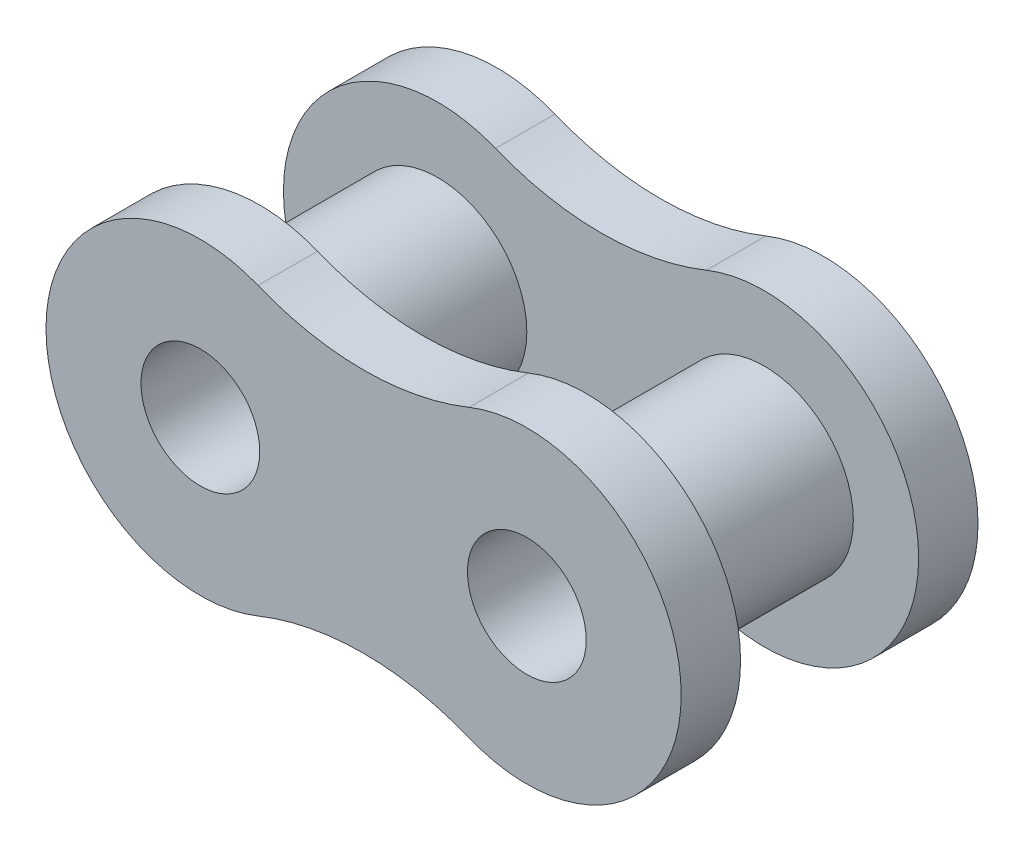
SolidWorks part; units mm, degrees
ref_plane "Front Plane" through (0, 0, 0) normal (0, 0, 1) x (1, 0, 0)
ref_plane "Top Plane" through (0, 0, 0) normal (0, 1, 0) x (1, 0, 0)
ref_plane "Right Plane" through (0, 0, 0) normal (1, 0, 0) x (0, 0, -1)
sketch "Sketch1" plane through (0, 0, 0) normal (0, 0, 1) x (1, 0, 0)
  line L0 (-41.1921, 0) -> (56.3425, 0) construction
  line L2 (-33.0338, 2.6) -> (-33.0338, 8.8923) construction
  arc A0 (-34.8111, 2.4112) -> (-34.8111, -2.4112) centre (-35.7838, 0) ccw
  arc A1 (-31.2566, -2.4112) -> (-31.2566, 2.4112) centre (-30.2838, 0) ccw
  arc A2 (-34.8111, 2.4112) -> (-31.2566, 2.4112) centre (-33.0338, 6.8162) ccw
  arc A3 (-34.8111, -2.4112) -> (-31.2566, -2.4112) centre (-33.0338, -6.8162) cw
  circle A4 centre (-35.7838, 0) radius 1
  circle A5 centre (-30.2838, 0) radius 1
  dimension "D1" = 5.5
extrude "Boss-Extrude1" add sketch "Sketch1" along normal blind 1
ref_plane "Plane1" through (0, 0, -1.5) normal (0, 0, -1) x (-1, 0, 0)
mirror "Mirror2" about plane through (0, 0, -1.5) normal (0, 0, -1) of bodies 101
sketch "Sketch2" plane through (0, 0, 1) normal (0, 0, 1) x (1, 0, 0)
  circle A0 centre (-30.2838, 0) radius 1
  circle A1 centre (-30.2838, 0) radius 1.5
  circle A2 centre (-35.7838, 0) radius 1
  circle A3 centre (-35.7838, 0) radius 1.5
extrude "Boss-Extrude2" add sketch "Sketch2" against normal blind 5
